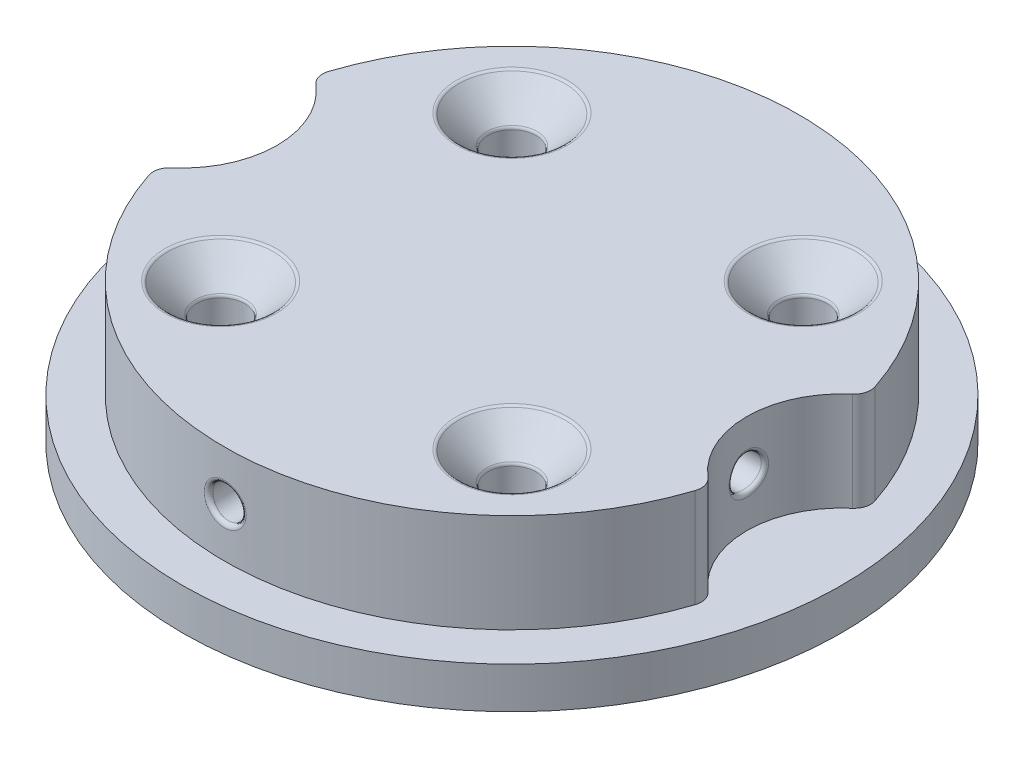
SolidWorks part; units mm, degrees
ref_plane "Front Plane" through (0, 0, 0) normal (0, 0, 1) x (1, 0, 0)
ref_plane "Top Plane" through (0, 0, 0) normal (0, 1, 0) x (1, 0, 0)
ref_plane "Right Plane" through (0, 0, 0) normal (1, 0, 0) x (0, 0, -1)
sketch "Sketch1" plane through (0, 0, 0) normal (0, 1, 0) x (1, 0, 0)
  circle A0 centre (0, 0) radius 40
  dimension "D1" = 80
extrude "Boss-Extrude1" add sketch "Sketch1" along normal blind 5
sketch "Sketch2" plane through (0, 5, 0) normal (0, 1, 0) x (1, 0, 0)
  line L0 (0, 0) -> (0, 24.601) construction
  arc A0 (-33.572, -9.5358) -> (33.572, -9.5358) centre (0, 0) ccw
  arc A1 (-33.572, -9.5358) -> (-33.572, 9.5358) centre (-40, 0) ccw
  arc A2 (33.572, -9.5358) -> (33.572, 9.5358) centre (40, 0) cw
  arc A3 (33.572, 9.5358) -> (-33.572, 9.5358) centre (0, 0) ccw
  dimension "D1" = 69.8
  dimension "D2" = 23
  dimension "D3" = 40
extrude "Boss-Extrude2" add sketch "Sketch2" along normal blind 12
sketch "Sketch3" plane through (0, 17, 0) normal (0, 1, 0) x (1, 0, 0)
  line L0 (0, 0) -> (0, 27.5674) construction
  line L1 (-17.6777, 17.6777) -> (0, 0) construction
  circle A0 centre (-17.6777, 17.6777) radius 2.93
  circle A1 centre (17.6777, 17.6777) radius 2.93
  circle A2 centre (17.6777, -17.6777) radius 2.93
  circle A3 centre (-17.6777, -17.6777) radius 2.93
  point P15 (0, 0)
  dimension "D1" = 5.86
  dimension "D2" = 25
  dimension "D3" = 45
  dimension "D4" = 4
extrude "Cut-Extrude1" cut sketch "Sketch3" against normal through all
sketch "Sketch4" plane through (0, 17, 0) normal (0, 1, 0) x (1, 0, 0)
  circle A0 centre (-17.6777, 17.6777) radius 6.58
  point P12 (0, 0)
  dimension "D1" = 13.16
ref_plane "Plane1" through (0, 13.35, 0) normal (0, 1, 0) x (1, 0, 0)
sketch "Sketch5" plane through (0, 13.35, 0) normal (0, 1, 0) x (1, 0, 0)
  circle A0 centre (-17.6777, 17.6777) radius 2.93
  dimension "D1" = 5.86
loft "Cut-Loft1" cut profiles "Sketch5", "Sketch4"
pattern_circular "CirPattern1" count 4 over 360 about axis through (0, 0, 0) along (0, 1, 0) of "Cut-Loft1"
sketch "Sketch9" plane through (0, 0, 0) normal (0, 0, 1) x (1, 0, 0)
  line L0 (33.572, 17) -> (-33.572, 17) construction
  circle A0 centre (0, 11) radius 2
  dimension "D1" = 4
  dimension "D2" = 6
extrude "Cut-Extrude3" cut sketch "Sketch9" along normal through all from offset 20
pattern_circular "CirPattern2" count 4 over 360 about axis through (0, 0, 0) along (0, 1, 0) of "Cut-Extrude3"
fillet "Fillet2" radius 0.5 16 edges at (1.9472, 11.4563, 34.8456) (-1.9472, 11.4563, -34.8456) (28.6672, 11.4264, -1.954) (-28.6672, 11.4264, 1.954) (11.0977, 17, -17.6777) (14.7477, 13.35, -17.6777) (17.6777, 17, 11.0977) (17.6777, 13.35, 14.7477) (-11.0977, 17, 17.6777) (-14.7477, 13.35, 17.6777) (-17.6777, 17, -11.0977) (-17.6777, 13.35, -14.7477) (17.6777, 0, 20.6077) (17.6777, 0, -14.7477) (-17.6777, 0, -14.7477) (-17.6777, 0, 20.6077)
fillet "Fillet4" radius 2 4 edges at (33.572, 11, 9.5358) (33.572, 11, -9.5358) (-33.572, 11, 9.5358) (-33.572, 11, -9.5358)
